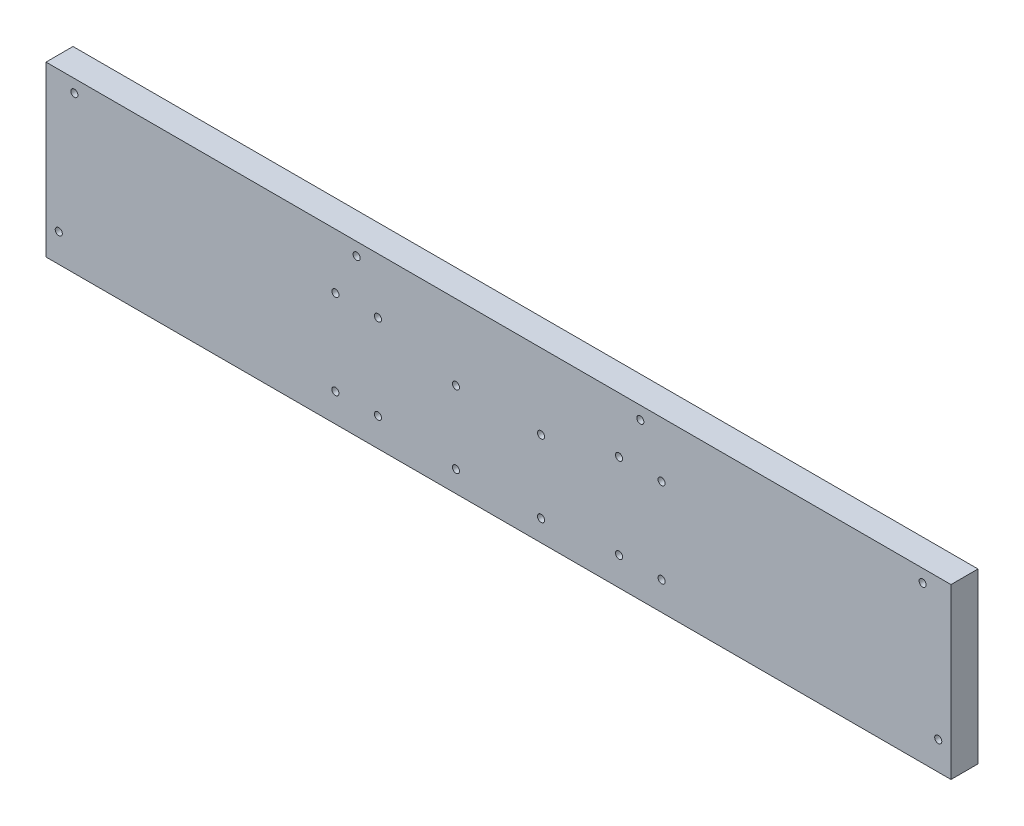
SolidWorks part; units mm, degrees
ref_plane "Front Plane" through (0, 0, 0) normal (0, 0, 1) x (1, 0, 0)
ref_plane "Top Plane" through (0, 0, 0) normal (0, 1, 0) x (1, 0, 0)
ref_plane "Right Plane" through (0, 0, 0) normal (1, 0, 0) x (0, 0, -1)
sketch "Sketch1" plane through (0, 0, 0) normal (0, 0, 1) x (1, 0, 0)
  line L1 (0, 119.05) -> (-638.1, 119.05)
  line L2 (0, 119.05) -> (0, 0)
  line L3 (0, 0) -> (-638.1, 0)
  line L4 (-638.1, 119.05) -> (-638.1, 0)
  dimension "D1" = 119.05
  dimension "D2" = 638.1
extrude "Boss-Extrude1" add sketch "Sketch1" along normal blind 19.05
sketch "Sketch4" plane through (0, 0, 19.05) normal (0, 0, 1) x (1, 0, 0)
  line L0 (-638.1, 0) -> (-638.1, 119.05)
  line L1 (-319.05, 0) -> (-319.05, 58.68)
  line L2 (-638.1, 0) -> (0, 0) construction
  line L3 (-638.1, 59.525) -> (0, 59.525)
  line L4 (0, 0) -> (0, 119.05) construction
  circle A6 centre (-9, 20) radius 2.5
  circle A7 centre (-20, 110.05) radius 2.5
  circle A8 centre (-219.05, 110.05) radius 2.5
  circle A9 centre (-419.05, 110.05) radius 2.5
  circle A10 centre (-618.1, 110.05) radius 2.5
  circle A11 centre (-629.1, 20) radius 2.5
hole_wizard "Ø5.0mm Dowel Hole1" positions "Sketch2" profile "Sketch3" hole size "Ø5.0" standard "ANSI Metric"
sketch "Sketch2" plane through (0, 0, 0) normal (0, 0, -1) x (-1, 0, 0)
  point P0 (434.05, 20)
  point P3 (404.05, 20)
  point P6 (404.05, 80)
  point P9 (434.05, 80)
  point P12 (349.05, 15)
  point P15 (349.05, 66)
  point P18 (289.05, 66)
  point P25 (289.05, 15)
  point P28 (234.05, 20)
  point P31 (234.05, 80)
  point P34 (204.05, 80)
  point P37 (204.05, 20)
  point P40 (629.1, 20)
  point P43 (618.1, 110.05)
  point P46 (419.05, 110.05)
  point P49 (219.05, 110.05)
  point P52 (20, 110.05)
  point P55 (9, 20)
sketch "Sketch3" plane through (-434.05, 20, 0) normal (1, 0, 0) x (0, 1, 0)
  line L0 (0, 0) -> (0, 30)
  line L1 (0, 30) -> (2.5, 28.4978)
  line L2 (2.5, 28.4978) -> (2.5, 0)
  line L5 (2.5, 0) -> (0, 0)
  line L10 (0, 30) -> (-2.5, 28.4978) construction
  line L11 (0, -6.35) -> (0, 107.95) construction
  dimension "Hole Dia." = 5
  dimension "Hole Depth" = 30
  dimension "Drill Angle" = 118
